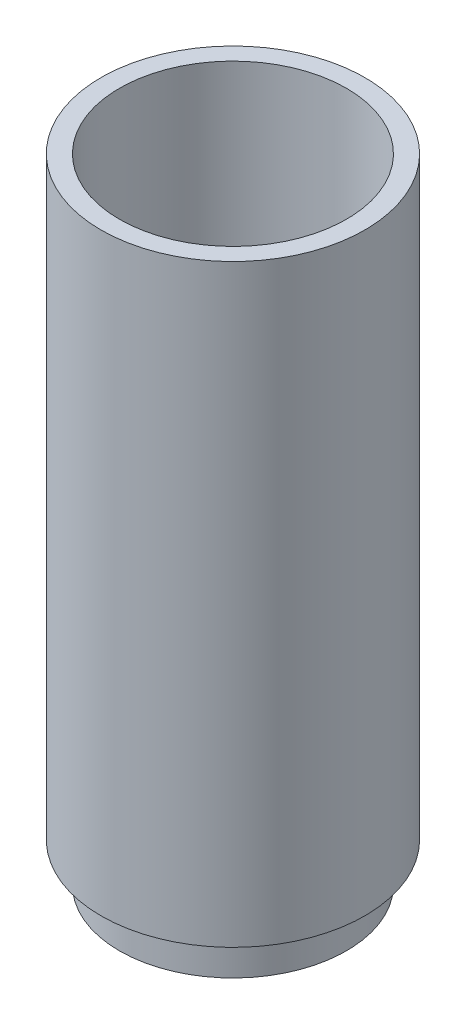
SolidWorks part; units mm, degrees
ref_plane "Front Plane" through (0, 0, 0) normal (0, 0, 1) x (1, 0, 0)
ref_plane "Top Plane" through (0, 0, 0) normal (0, 1, 0) x (1, 0, 0)
ref_plane "Right Plane" through (0, 0, 0) normal (1, 0, 0) x (0, 0, -1)
sketch "Sketch1" plane through (0, 0, 0) normal (0, 1, 0) x (1, 0, 0)
  circle A0 centre (0, 0) radius 50
  dimension "D1" = 100
extrude "Boss-Extrude1" add sketch "Sketch1" along normal blind 225
shell "Shell1" thickness 7
sketch "Sketch2" plane through (0, 0, 0) normal (0, -1, 0) x (1, 0, 0)
  circle A1 centre (0, 0) radius 43
  circle A2 centre (0, 0) radius 43
  dimension "D1" = 0
extrude "Boss-Extrude2" add sketch "Sketch2" along normal blind 15
